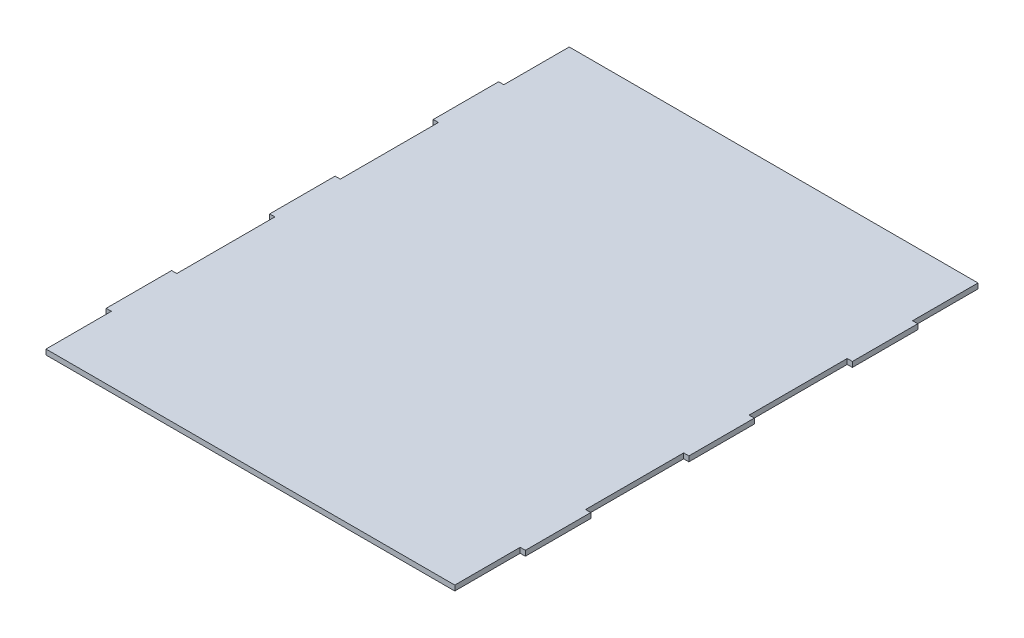
SolidWorks part; units mm, degrees
ref_plane "前视" through (0, 0, 0) normal (0, 0, 1) x (1, 0, 0)
ref_plane "上视" through (0, 0, 0) normal (0, 1, 0) x (1, 0, 0)
ref_plane "右视" through (0, 0, 0) normal (1, 0, 0) x (0, 0, -1)
sketch "Sketch1" plane through (0, 0, 0) normal (0, 1, 0) x (1, 0, 0)
  line L1 (0, 0) -> (250, 0)
  line L2 (0, 0) -> (0, -320)
  line L3 (0, -320) -> (250, -320)
  line L4 (250, 0) -> (250, -320)
  dimension "D1" = 320
  dimension "D2" = 250
extrude "Boss-Extrude1" add sketch "Sketch1" along normal blind 3.175
sketch "Sketch2" plane through (0, 3.175, 0) normal (0, 1, 0) x (1, 0, 0)
  line L0 (0, 0) -> (0, -320) construction
  line L1 (0, -40) -> (-3.175, -40)
  line L2 (0, -40) -> (0, -80)
  line L3 (0, -80) -> (-3.175, -80)
  line L4 (-3.175, -40) -> (-3.175, -80)
  line L5 (250, 0) -> (0, 0) construction
  line L6 (250, -320) -> (250, 0) construction
  line L7 (250, -40) -> (253.175, -40)
  line L8 (250, -40) -> (250, -80)
  line L9 (250, -80) -> (253.175, -80)
  line L10 (253.175, -40) -> (253.175, -80)
  line L11 (250, -140) -> (250, -180)
  line L12 (250, -140) -> (253.175, -140)
  line L13 (253.175, -140) -> (253.175, -180)
  line L14 (250, -180) -> (253.175, -180)
  line L15 (0, -140) -> (-3.175, -140)
  line L16 (-3.175, -140) -> (-3.175, -180)
  line L17 (0, -140) -> (0, -180)
  line L18 (0, -180) -> (-3.175, -180)
  line L19 (250, -240) -> (250, -280)
  line L20 (250, -240) -> (253.175, -240)
  line L21 (253.175, -240) -> (253.175, -280)
  line L22 (250, -280) -> (253.175, -280)
  line L23 (0, -240) -> (-3.175, -240)
  line L24 (-3.175, -240) -> (-3.175, -280)
  line L25 (0, -240) -> (0, -280)
  line L26 (0, -280) -> (-3.175, -280)
  dimension "D1" = 40
  dimension "D2" = 40
  dimension "D3" = 3.175
  dimension "D4" = 3.175
  dimension "D5" = 3
extrude "Boss-Extrude2" add sketch "Sketch2" against normal up to surface (3.175 mm away) up to face at (125, 0, 160)
